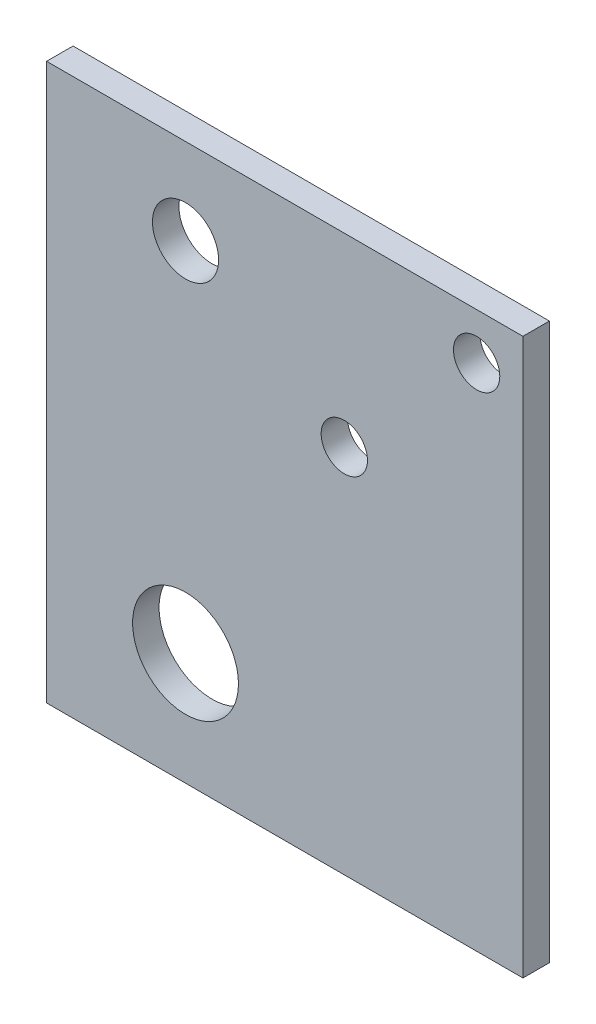
SolidWorks part; units mm, degrees
material "SKD11淬火HRC56-60"
ref_plane "前基準面" through (0, 0, 0) normal (0, 0, 1) x (1, 0, 0)
ref_plane "上基準面" through (0, 0, 0) normal (0, 1, 0) x (1, 0, 0)
ref_plane "右基準面" through (0, 0, 0) normal (1, 0, 0) x (0, 0, -1)
sketch "草图1" plane through (0, 0, 0) normal (0, 0, 1) x (1, 0, 0)
  line L1 (0, 0) -> (36, 0)
  line L2 (0, 0) -> (0, 42)
  line L3 (0, 42) -> (36, 42)
  line L4 (36, 0) -> (36, 42)
  dimension "D1" = 42
  dimension "D2" = 36
extrude "凸台-拉伸1" add sketch "草图1" along normal blind 2
sketch "草图2" plane through (0, 0, 2) normal (0, 0, 1) x (1, 0, 0)
  circle A0 centre (32.5, 38.5) radius 1.75
  circle A1 centre (22.5, 28) radius 1.75
  circle A2 centre (10.5, 35.5) radius 2.5
  dimension "D1" = 3.5
  dimension "D2" = 5
extrude "切除-拉伸1" cut sketch "草图2" against normal through all
sketch "草图3" plane through (0, 0, 2) normal (0, 0, 1) x (1, 0, 0)
  line L0 (10.5, 33) -> (10.5, 4.9712) construction
  circle A0 centre (10.5, 8.5) radius 4
  circle A1 centre (10.5, 35.5) radius 2.5 construction
  dimension "D1" = 8
  dimension "D2" = 27
extrude "切除-拉伸2" cut sketch "草图3" against normal through all
